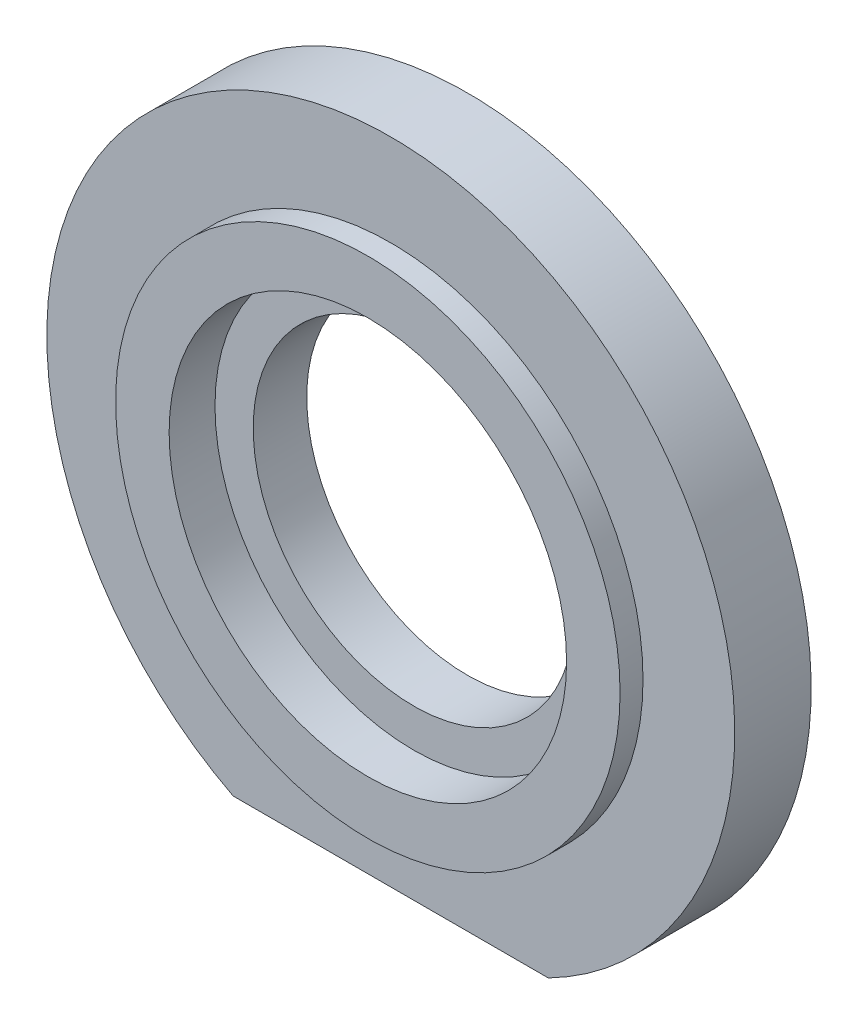
SolidWorks part; units mm, degrees
ref_plane "前视基准面" through (0, 0, 0) normal (0, 0, 1) x (1, 0, 0)
ref_plane "上视基准面" through (0, 0, 0) normal (0, 1, 0) x (1, 0, 0)
ref_plane "右视基准面" through (0, 0, 0) normal (1, 0, 0) x (0, 0, -1)
sketch "草图1" plane through (0, 0, 0) normal (0, 0, 1) x (1, 0, 0)
  line L0 (0, -33.3908) -> (0, 33.3908) construction
  circle A0 centre (0, 29.4568) radius 45
  circle A1 centre (0, 29.4568) radius 21
  dimension "D1" = 90
  dimension "D2" = 42
extrude "凸台-拉伸1" add sketch "草图1" along normal blind 10
sketch "草图2" plane through (0, 0, 10) normal (0, 0, 1) x (1, 0, 0)
  circle A0 centre (0, 29.4568) radius 33
  circle A1 centre (0, 29.4568) radius 21
  dimension "D1" = 66
sketch "草图4" plane through (0, 0, 0) normal (0, 0, -1) x (-1, 0, 0)
  line L0 (-20.6155, -10.5432) -> (20.6155, -10.5432)
  arc A0 (-20.6155, -10.5432) -> (20.6155, -10.5432) centre (0, 29.4568) ccw
  dimension "D1" = 90
  dimension "D2" = 40
extrude "凸台-拉伸2" add sketch "草图2" along normal blind 3
extrude "切除-拉伸1" cut sketch "草图4" against normal through all
sketch "草图5" plane through (0, 0, 13) normal (0, 0, 1) x (1, 0, 0)
  circle A0 centre (0, 29.4568) radius 26
  dimension "D1" = 52
extrude "切除-拉伸2" cut sketch "草图5" against normal blind 6
